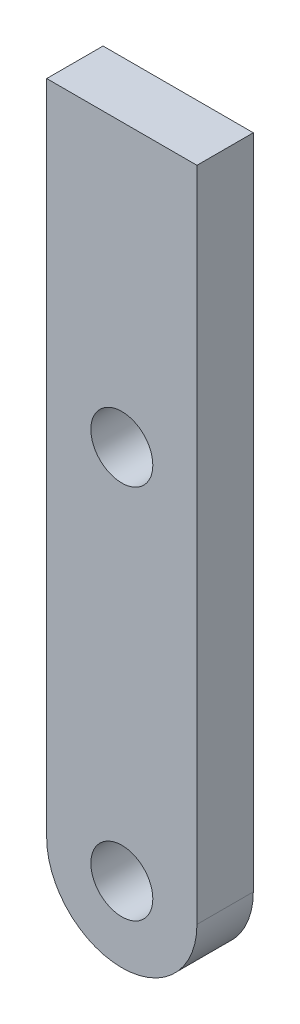
SolidWorks part; units mm, degrees
ref_plane "前视基准面" through (0, 0, 0) normal (0, 0, 1) x (1, 0, 0)
ref_plane "上视基准面" through (0, 0, 0) normal (0, 1, 0) x (1, 0, 0)
ref_plane "右视基准面" through (0, 0, 0) normal (1, 0, 0) x (0, 0, -1)
sketch "草图1" plane through (0, 0, 0) normal (0, 0, 1) x (1, 0, 0)
  line L0 (0, 10) -> (0, -10) construction
  line L2 (4, 10) -> (4, -10)
  line L3 (-4, 10) -> (-4, -10)
  arc A0 (4, 10) -> (-4, 10) centre (0, 10) ccw
  arc A1 (-4, -10) -> (4, -10) centre (0, -10) ccw
  circle A2 centre (0, 10) radius 1.65
  circle A3 centre (0, -10) radius 1.65
  point P5 (0, 0)
  dimension "D2" = 4
  dimension "D3" = 3.3
  dimension "D4" = 3.3
  dimension "D1" = 20
extrude "凸台-拉伸1" add sketch "草图1" along normal blind 3
sketch "草图2" plane through (0, 0, 3) normal (0, 0, 1) x (1, 0, 0)
  line L0 (-4, 10) -> (-4, 25)
  line L2 (-4, 25) -> (4, 25)
  line L3 (4, 25) -> (4, 10)
  line L4 (4, -10) -> (4, 10) construction
  circle A0 centre (0, 10) radius 1.65 construction
  arc A1 (4, 10) -> (-4, 10) centre (0, 10) ccw construction
  arc A2 (4, 10) -> (-4, 10) centre (0, 10) ccw
  dimension "D1" = 15
extrude "凸台-拉伸2" add sketch "草图2" against normal up to surface (3 mm away) up to face at (0, 0, 0)
